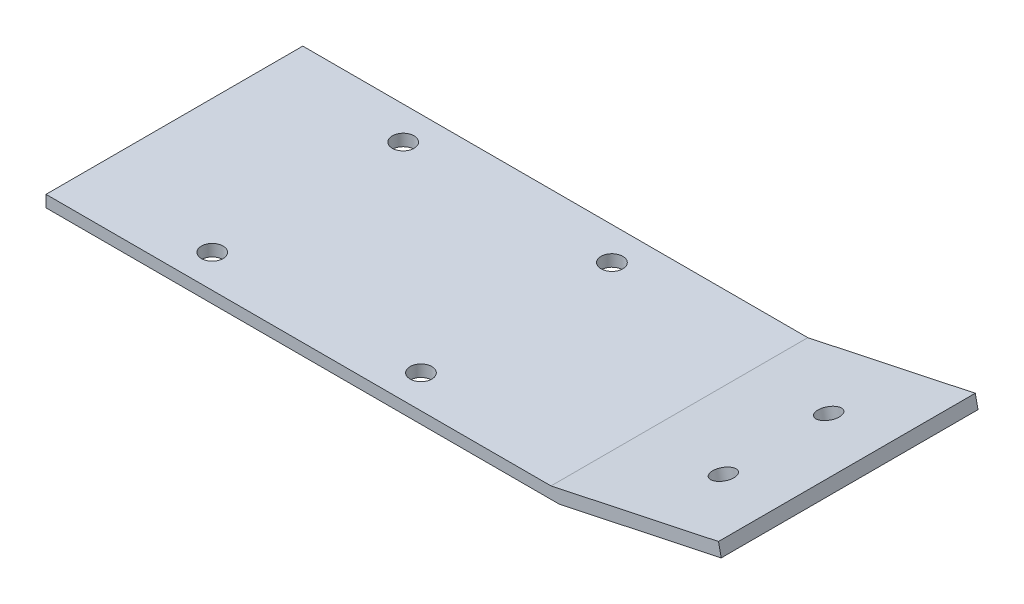
SolidWorks part; units mm, degrees
ref_plane "前视基准面" through (0, 0, 0) normal (0, 0, 1) x (1, 0, 0)
ref_plane "上视基准面" through (0, 0, 0) normal (0, 1, 0) x (1, 0, 0)
ref_plane "右视基准面" through (0, 0, 0) normal (1, 0, 0) x (0, 0, -1)
sketch "草图1" plane through (0, 0, 0) normal (0, 0, 1) x (1, 0, 0)
  line L6 (0, 0) -> (77.9407, 0)
  line L7 (77.9407, 0) -> (102.5477, 5.2304)
  line L8 (102.5477, 5.2304) -> (102.1318, 7.1867)
  line L9 (102.1318, 7.1867) -> (76.7, 1.781)
  line L10 (76.7, 1.781) -> (0, 1.781)
  line L11 (0, 1.781) -> (0, 0)
  dimension "D1" = 168
  dimension "D2" = 2
  dimension "D3" = 76.7
  dimension "D4" = 26
extrude "凸台-拉伸1" add sketch "草图1" along normal blind 39
sketch "草图3" plane through (2.9533, -13.8944, 0) normal (-0.2079, 0.9781, 0) x (0.9781, 0.2079, 0)
  line L0 (101.3942, -39) -> (75.3942, -39) construction
  line L1 (75.3942, -39) -> (75.3942, 0) construction
  circle A0 centre (90.3942, -11.5) radius 1.65
  circle A1 centre (90.3942, -27.5) radius 1.65
  dimension "D1" = 16
  dimension "D2" = 11.5
  dimension "D4" = 3.3
  dimension "D5" = 3.3
  dimension "D6" = 15
  dimension "D3" = 15
extrude "切除-拉伸1" cut sketch "草图3" against normal blind 10
sketch "草图4" plane through (0, 1.781, 0) normal (0, 1, 0) x (1, 0, 0)
  line L0 (0, -39) -> (0, 0) construction
  line L1 (76.7, 0) -> (0, 0) construction
  line L2 (76.7, -39) -> (0, -39) construction
  circle A2 centre (20.25, -5) radius 1.65
  circle A3 centre (51.95, -5) radius 1.65
  circle A4 centre (51.95, -34) radius 1.65
  circle A5 centre (20.25, -34) radius 1.65
  dimension "D1" = 20.25
  dimension "D2" = 31.7
  dimension "D4" = 31.7
  dimension "D5" = 20.25
  dimension "D6" = 5
  dimension "D3" = 5
extrude "切除-拉伸2" cut sketch "草图4" against normal blind 10
